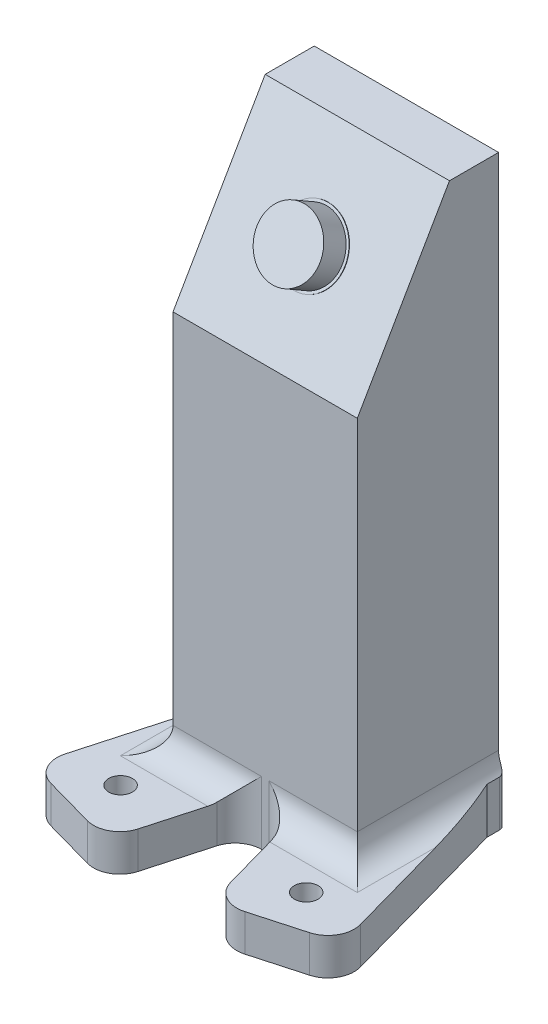
SolidWorks part; units mm, degrees
ref_plane "Ebene vorne" through (0, 0, 0) normal (0, 0, 1) x (1, 0, 0)
ref_plane "Ebene oben" through (0, 0, 0) normal (0, 1, 0) x (1, 0, 0)
ref_plane "Ebene rechts" through (0, 0, 0) normal (1, 0, 0) x (0, 0, -1)
sketch "Skizze1" plane through (0, 0, 0) normal (1, 0, 0) x (0, 0, -1)
  line L0 (0, 0) -> (17.5, 0)
  line L1 (0, 0) -> (0, 80)
  line L2 (0, 80) -> (17.5, 110.3109)
  line L3 (17.5, 110.3109) -> (17.5, 0) construction
  line L4 (17.5, 0) -> (26.82, 0)
  line L5 (26.82, 0) -> (26.82, 110.3109)
  line L6 (26.82, 110.3109) -> (17.5, 110.3109)
  dimension "D1" = 60
  dimension "D2" = 80
  dimension "D3" = 35
  dimension "D4" = 26.82
extrude "Aufsatz-Linear austragen1" add sketch "Skizze1" along normal blind 35
sketch "Skizze3" plane through (0, 20, 34.641) normal (0, 0.5, 0.866) x (1, 0, 0)
  line L0 (0, 104.282) -> (35, 69.282) construction
  line L1 (17.5, 86.782) -> (35, 104.282) construction
  line L2 (35, 104.282) -> (0, 104.282) construction
  line L3 (35, 104.282) -> (35, 69.282) construction
  circle A0 centre (17.5, 86.782) radius 6
  dimension "D1" = 12
extrude "Aufsatz-Linear austragen2" add sketch "Skizze3" along normal blind 5
sketch "Skizze4" plane through (0, 20, 34.641) normal (0, 0.5, 0.866) x (1, 0, 0)
  circle A0 centre (17.5, 86.782) radius 6.5
  dimension "D1" = 13
extrude "Aufsatz-Linear austragen3" add sketch "Skizze4" along normal blind 0.1
ref_plane "Ebene1" through (0, 80, 0) normal (0, -1, 0) x (-1, 0, 0)
ref_plane "Ebene2" through (0, 4.5, 0) normal (0, 1, 0) x (1, 0, 0)
sketch "Skizze7" plane through (0, 4.5, 0) normal (0, -1, 0) x (-1, 0, 0)
  line L0 (-35, 26.82) -> (0, 26.82) construction
  line L1 (-35, 0) -> (0, 26.82) construction
  line L2 (-17.5, 13.41) -> (-17.5, 26.82) construction
  line L4 (-17.5, 13.41) -> (-35, 13.41) construction
  line L5 (-35, 0) -> (-35, 26.82) construction
  circle A0 centre (-28.5, 5) radius 2.85
  circle A1 centre (-6.5, 5) radius 2.85
  circle A2 centre (-6.5, 21.82) radius 2.85
  circle A3 centre (-28.5, 21.82) radius 2.85
  dimension "D1" = 5.7
  dimension "D2" = 11
  dimension "D3" = 5
extrude "Schnitt-Linear austragen1" [suppressed] cut sketch "Skizze7" against normal through all
hole_wizard "Ø3.4 (3.4) Durchmesser Bohrung1" [suppressed] positions "3D-Skizze3" profile "Skizze8" hole size "Ø3.4" standard "DIN"
sketch3d "3D-Skizze3" [suppressed]
  line L0 (6.5, 101.5966, -5) -> (6.5, 4.5, -5) construction
  line L1 (6.5, 118.3109, -21.82) -> (6.5, 4.5, -21.82) construction
  line L2 (28.5, 118.3109, -21.82) -> (28.5, 4.5, -21.82) construction
  line L3 (28.5, 101.5966, -5) -> (28.5, 4.5, -5) construction
  point P0 (6.5, 4.5, -5)
  point P4 (6.5, 4.5, -21.82)
  point P8 (28.5, 4.5, -21.82)
  point P12 (28.5, 4.5, -5)
sketch "Skizze8" plane through (6.5, 4.5, -5) normal (1, 0, 0) x (0, 0, 1)
  line L0 (0, 0) -> (0, 4.5)
  line L1 (0, 4.5) -> (1.7, 4.5)
  line L2 (1.7, 4.5) -> (1.7, 0)
  line L5 (1.7, 0) -> (0, 0)
  line L11 (0, -6.35) -> (0, 107.95) construction
  dimension "Bohrerdurchmesser" = 3.4
  dimension "Bohrungstiefe" = 4.5
sketch "Skizze9" plane through (0, 0, 0) normal (0, -1, 0) x (1, 0, 0)
  circle A0 centre (17.4988, -21.6442) radius 1.425
  dimension "D1" = 2.85
extrude "Schnitt-Linear austragen2" cut sketch "Skizze9" against normal blind 10
sketch "Skizze10" plane through (0, 0, 0) normal (0, -1, 0) x (1, 0, 0)
  line L0 (35, -26.82) -> (36.2227, -26.82)
  line L1 (36.2227, -26.82) -> (36.2227, -23.3967)
  line L2 (36.2227, -23.3967) -> (46.8899, 14.7774)
  line L3 (117.4988, 267.461) -> (36.7609, -21.4705) construction
  line L4 (46.8899, 14.7774) -> (27.6278, 20.1599)
  line L5 (98.2367, 272.8435) -> (17.4988, -16.088) construction
  line L6 (27.6278, 20.1599) -> (21.9944, 0)
  line L7 (35, 0) -> (0, 0) construction
  line L8 (21.9944, 0) -> (35, -26.82)
  line L9 (17.5, 0) -> (17.5, -4.1312) construction
  line L10 (-1.2227, -26.82) -> (-1.2227, -23.3967)
  line L11 (0, -26.82) -> (-1.2227, -26.82)
  line L12 (13.0056, 0) -> (0, -26.82)
  line L13 (-1.2227, -23.3967) -> (-11.8899, 14.7774)
  line L14 (7.3722, 20.1599) -> (13.0056, 0)
  line L15 (-11.8899, 14.7774) -> (7.3722, 20.1599)
  line L16 (25.4933, 12.5213) -> (44.7554, 7.1388) construction
  circle A0 centre (35.1244, 9.83) radius 2.25
  circle A1 centre (-0.1244, 9.83) radius 2.25
  dimension "D1" = 4.5
extrude "Aufsatz-Linear austragen4" add sketch "Skizze10" against normal blind 7
fillet "Verrundung1" radius 5 10 edges at (6.5028, 7, 0) (28.4972, 7, 0) (35, 7, -13.41) (0, 7, -13.41) (-11.8899, 3.5, 14.7774) (7.3722, 3.5, 20.1599) (46.8899, 3.5, 14.7774) (27.6278, 3.5, 20.1599) (21.9944, 3.5, 0) (13.0056, 3.5, 0)
fillet "Verrundung2" radius 1 2 edges at (-1.2227, 4.362, -26.82) (36.2227, 4.362, -26.82)
